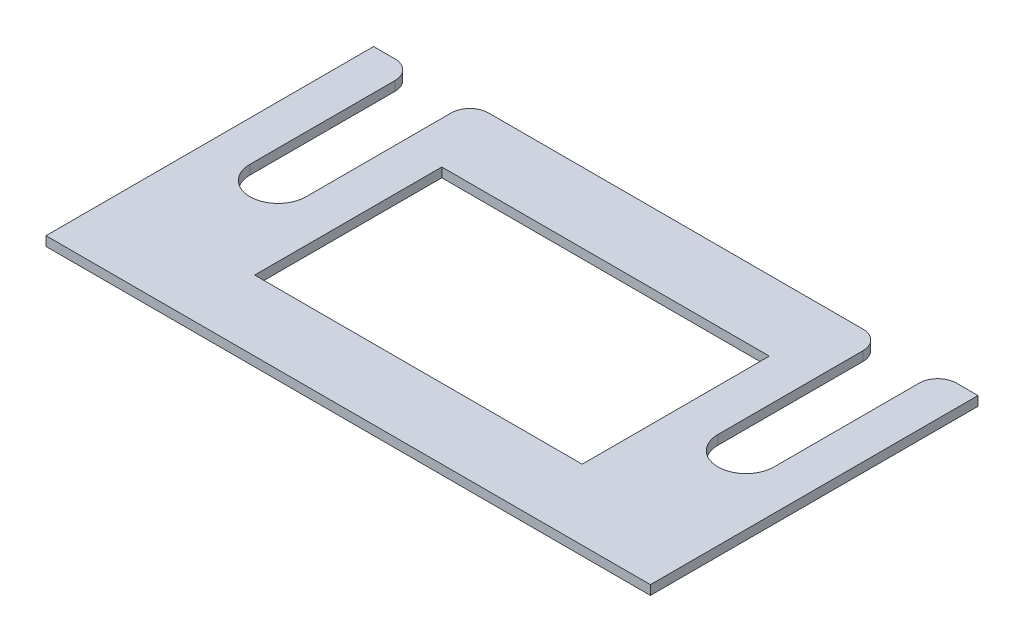
SolidWorks part; units mm, degrees
material "1060 Alloy"
ref_plane "Front Plane" through (0, 0, 0) normal (0, 0, 1) x (1, 0, 0)
ref_plane "Top Plane" through (0, 0, 0) normal (0, 1, 0) x (1, 0, 0)
ref_plane "Right Plane" through (0, 0, 0) normal (1, 0, 0) x (0, 0, -1)
sketch "Sketch1" plane through (0, 0, 0) normal (0, 1, 0) x (1, 0, 0)
  line L1 (-32.29, -17.5) -> (32.29, -17.5)
  line L2 (-32.29, -17.5) -> (-32.29, 17.5)
  line L3 (-32.29, 17.5) -> (32.29, 17.5)
  line L4 (32.29, -17.5) -> (32.29, 17.5)
  line L5 (-32.29, -17.5) -> (32.29, 17.5) construction
  line L6 (-32.29, 17.5) -> (32.29, -17.5) construction
  circle A2 centre (-25, 0) radius 3
  circle A3 centre (25, 0) radius 3
  point P0 (0, 0)
  dimension "D1" = 64.58
  dimension "D3" = 6
  dimension "D4" = 6
  dimension "D6" = 25
  dimension "D2" = 35
  dimension "D5" = 50
extrude "Boss-Extrude1" add sketch "Sketch1" along normal blind 1
sketch "Sketch2" plane through (0, 1, 0) normal (0, 1, 0) x (1, 0, 0)
  line L1 (-22, 0) -> (-28, 0)
  line L2 (-22, 0) -> (-22, 17.5)
  line L3 (-22, 17.5) -> (-28, 17.5)
  line L4 (-28, 0) -> (-28, 17.5)
  line L5 (22, 0) -> (28, 0)
  line L7 (22, 0) -> (22, 17.5)
  line L10 (28, 0) -> (28, 17.5)
  line L11 (32.29, 17.5) -> (-32.29, 17.5) construction
  line L12 (28, 17.5) -> (22, 17.5)
  circle A0 centre (-25, 0) radius 3 construction
  circle A1 centre (25, 0) radius 3 construction
  point P18 (25, 0)
extrude "Cut-Extrude1" cut sketch "Sketch2" against normal through all both and the other way through all
fillet "Fillet1" radius 2 4 edges at (22, 0.5, -17.5) (-28, 0.5, -17.5) (-22, 0.5, -17.5) (28, 0.5, -17.5)
sketch "Sketch3" plane through (0, 0, 0) normal (0, -1, 0) x (1, 0, 0)
  line L1 (17.5, -10) -> (-17.5, -10)
  line L2 (17.5, -10) -> (17.5, 10)
  line L3 (17.5, 10) -> (-17.5, 10)
  line L4 (-17.5, -10) -> (-17.5, 10)
  line L5 (17.5, -10) -> (-17.5, 10) construction
  line L6 (17.5, 10) -> (-17.5, -10) construction
  point P0 (0, 0)
  dimension "D1" = 35
  dimension "D2" = 20
extrude "Cut-Extrude2" cut sketch "Sketch3" against normal through all both and the other way through all
